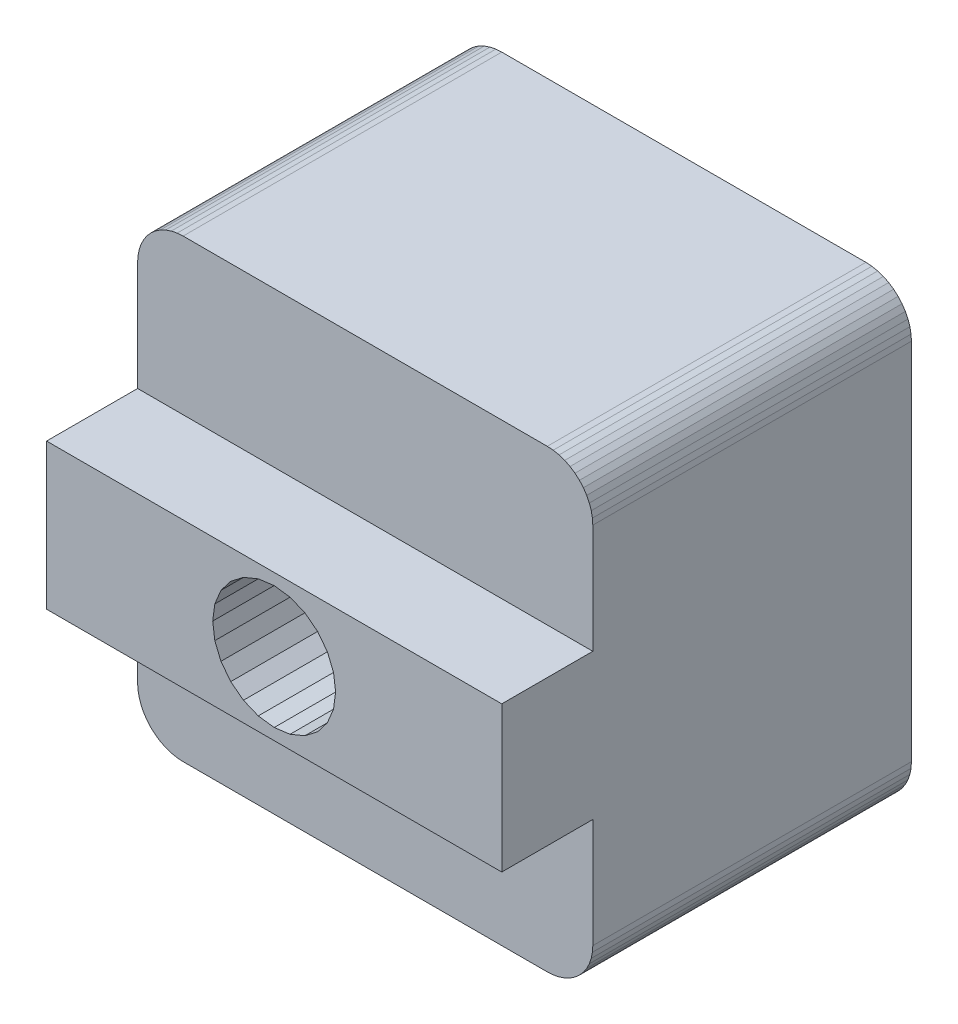
SolidWorks part; units mm, degrees
ref_plane "Front Plane" through (0, 0, 0) normal (0, 0, 1) x (1, 0, 0)
ref_plane "Top Plane" through (0, 0, 0) normal (0, 1, 0) x (1, 0, 0)
ref_plane "Right Plane" through (0, 0, 0) normal (1, 0, 0) x (0, 0, -1)
ref_plane "Plane1" through (0, 0, 7) normal (0, 0, 1) x (1, 0, 0)
sketch "Sketch1" plane through (0, 0, 7) normal (0, 0, 1) x (1, 0, 0)
  line L0 (84.366, 79.5) -> (84.2934, 79.6088)
  line L1 (84.2934, 79.6088) -> (84.2071, 79.7071)
  line L2 (84.2071, 79.7071) -> (84.1088, 79.7934)
  line L3 (84.1088, 79.7934) -> (84, 79.866)
  line L4 (84, 79.866) -> (83.8827, 79.9239)
  line L5 (83.8827, 79.9239) -> (83.7588, 79.9659)
  line L6 (83.7588, 79.9659) -> (83.6305, 79.9914)
  line L7 (83.6305, 79.9914) -> (83.5, 80)
  line L8 (83.5, 80) -> (75.5, 80)
  line L9 (75.5, 80) -> (75.3695, 79.9914)
  line L10 (75.3695, 79.9914) -> (75.2412, 79.9659)
  line L11 (75.2412, 79.9659) -> (75.1173, 79.9239)
  line L12 (75.1173, 79.9239) -> (75, 79.866)
  line L13 (75, 79.866) -> (74.8912, 79.7934)
  line L14 (74.8912, 79.7934) -> (74.7929, 79.7071)
  line L15 (74.7929, 79.7071) -> (74.7066, 79.6088)
  line L16 (74.7066, 79.6088) -> (74.634, 79.5)
  line L17 (74.634, 79.5) -> (74.5761, 79.3827)
  line L18 (74.5761, 79.3827) -> (74.5341, 79.2588)
  line L19 (74.5341, 79.2588) -> (74.5086, 79.1305)
  line L20 (74.5086, 79.1305) -> (74.5, 79)
  line L21 (74.5, 79) -> (74.5, 71)
  line L22 (74.5, 71) -> (74.5086, 70.8695)
  line L23 (74.5086, 70.8695) -> (74.5341, 70.7412)
  line L24 (74.5341, 70.7412) -> (74.5761, 70.6173)
  line L25 (74.5761, 70.6173) -> (74.634, 70.5)
  line L26 (74.634, 70.5) -> (74.7066, 70.3912)
  line L27 (74.7066, 70.3912) -> (74.7929, 70.2929)
  line L28 (74.7929, 70.2929) -> (74.8912, 70.2066)
  line L29 (74.8912, 70.2066) -> (75, 70.134)
  line L30 (75, 70.134) -> (75.1173, 70.0761)
  line L31 (75.1173, 70.0761) -> (75.2412, 70.0341)
  line L32 (75.2412, 70.0341) -> (75.3695, 70.0086)
  line L33 (75.3695, 70.0086) -> (75.5, 70)
  line L34 (75.5, 70) -> (83.5, 70)
  line L35 (83.5, 70) -> (83.6305, 70.0086)
  line L36 (83.6305, 70.0086) -> (83.7588, 70.0341)
  line L37 (83.7588, 70.0341) -> (83.8827, 70.0761)
  line L38 (83.8827, 70.0761) -> (84, 70.134)
  line L39 (84, 70.134) -> (84.1088, 70.2066)
  line L40 (84.1088, 70.2066) -> (84.2071, 70.2929)
  line L41 (84.2071, 70.2929) -> (84.2934, 70.3912)
  line L42 (84.2934, 70.3912) -> (84.366, 70.5)
  line L43 (84.366, 70.5) -> (84.4239, 70.6173)
  line L44 (84.4239, 70.6173) -> (84.4659, 70.7412)
  line L45 (84.4659, 70.7412) -> (84.4914, 70.8695)
  line L46 (84.4914, 70.8695) -> (84.5, 71)
  line L47 (84.5, 71) -> (84.5, 79)
  line L48 (84.5, 79) -> (84.4914, 79.1305)
  line L49 (84.4914, 79.1305) -> (84.4659, 79.2588)
  line L50 (84.4659, 79.2588) -> (84.4239, 79.3827)
  line L51 (84.4239, 79.3827) -> (84.366, 79.5)
extrude "Boss-Extrude1" add sketch "Sketch1" against normal blind 7
sketch "Sketch2" plane through (0, 0, 7) normal (0, 0, 1) x (1, 0, 0)
  line L0 (74.5, 76.6) -> (84.5, 76.6)
  line L1 (84.5, 76.6) -> (84.5, 73.4)
  line L2 (84.5, 73.4) -> (74.5, 73.4)
  line L3 (74.5, 73.4) -> (74.5, 76.6)
extrude "Boss-Extrude2" add sketch "Sketch2" along normal blind 2
sketch "Sketch3" plane through (0, 0, 0) normal (0, 0, -1) x (-1, 0, 0)
  line L0 (-80.4546, 75.9546) -> (-80.6691, 75.675)
  line L1 (-80.6691, 75.675) -> (-80.804, 75.3494)
  line L2 (-80.804, 75.3494) -> (-80.85, 75)
  line L3 (-80.85, 75) -> (-80.804, 74.6506)
  line L4 (-80.804, 74.6506) -> (-80.6691, 74.325)
  line L5 (-80.6691, 74.325) -> (-80.4546, 74.0454)
  line L6 (-80.4546, 74.0454) -> (-80.175, 73.8309)
  line L7 (-80.175, 73.8309) -> (-79.8494, 73.696)
  line L8 (-79.8494, 73.696) -> (-79.5, 73.65)
  line L9 (-79.5, 73.65) -> (-79.1506, 73.696)
  line L10 (-79.1506, 73.696) -> (-78.825, 73.8309)
  line L11 (-78.825, 73.8309) -> (-78.5454, 74.0454)
  line L12 (-78.5454, 74.0454) -> (-78.3309, 74.325)
  line L13 (-78.3309, 74.325) -> (-78.196, 74.6506)
  line L14 (-78.196, 74.6506) -> (-78.15, 75)
  line L15 (-78.15, 75) -> (-78.196, 75.3494)
  line L16 (-78.196, 75.3494) -> (-78.3309, 75.675)
  line L17 (-78.3309, 75.675) -> (-78.5454, 75.9546)
  line L18 (-78.5454, 75.9546) -> (-78.825, 76.1691)
  line L19 (-78.825, 76.1691) -> (-79.1506, 76.304)
  line L20 (-79.1506, 76.304) -> (-79.5, 76.35)
  line L21 (-79.5, 76.35) -> (-79.8494, 76.304)
  line L22 (-79.8494, 76.304) -> (-80.175, 76.1691)
  line L23 (-80.175, 76.1691) -> (-80.4546, 75.9546)
extrude "Cut-Extrude1" cut sketch "Sketch3" against normal through all
